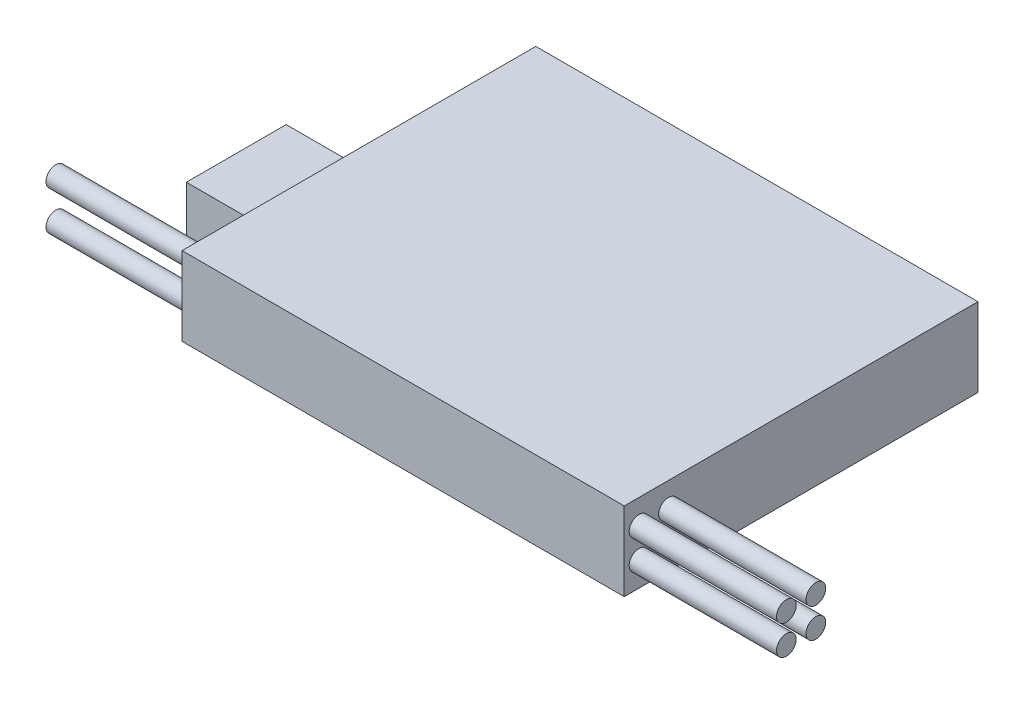
SolidWorks part; units mm, degrees
ref_plane "Plan de face" through (0, 0, 0) normal (0, 0, 1) x (1, 0, 0)
ref_plane "Plan de dessus" through (0, 0, 0) normal (0, 1, 0) x (1, 0, 0)
ref_plane "Plan de droite" through (0, 0, 0) normal (1, 0, 0) x (0, 0, -1)
sketch "Esquisse1" plane through (0, 0, 0) normal (0, 1, 0) x (1, 0, 0)
  line L1 (-22.5, 18) -> (22.5, 18)
  line L2 (-22.5, 18) -> (-22.5, -18)
  line L3 (-22.5, -18) -> (22.5, -18)
  line L4 (22.5, 18) -> (22.5, -18)
  point P4 (0, 18)
  point P6 (-22.5, 0)
  dimension "D1" = 36
  dimension "D2" = 45
extrude "Boss.-Extru.1" add sketch "Esquisse1" along normal blind 8
sketch "Esquisse2" plane through (-22.5, 0, 0) normal (-1, 0, 0) x (0, 0, 1)
  line L0 (18, 8) -> (18, 0) construction
  line L1 (1.4022, 7.81) -> (11.5622, 7.81)
  line L2 (1.4022, 7.81) -> (1.4022, 0.19)
  line L3 (1.4022, 0.19) -> (11.5622, 0.19)
  line L4 (11.5622, 7.81) -> (11.5622, 0.19)
  point P6 (18, 4)
  point P7 (11.5622, 4)
  dimension "D1" = 7.62
  dimension "D2" = 10.16
extrude "Boss.-Extru.2" add sketch "Esquisse2" along normal blind 6
sketch "Esquisse3" plane through (-22.5, 0, 0) normal (-1, 0, 0) x (0, 0, 1)
  line L0 (18, 4) -> (14.1664, 4) construction
  line L1 (18, 8) -> (18, 0) construction
  circle A0 centre (15.846, 6) radius 1
  circle A2 centre (15.846, 2) radius 1
  dimension "D1" = 2
  dimension "D2" = 4
extrude "Boss.-Extru.3" add sketch "Esquisse3" along normal blind 15
sketch "Esquisse4" plane through (22.5, 0, 0) normal (1, 0, 0) x (0, 0, -1)
  line L0 (-18, 4) -> (-15, 4) construction
  line L1 (-18, 8) -> (-18, 0) construction
  line L2 (-15, 8) -> (-15, 0) construction
  line L3 (-18, 8) -> (18, 8) construction
  line L4 (-18, 0) -> (18, 0) construction
  circle A0 centre (-16.5, 5.5) radius 1
  circle A2 centre (-16.5, 2.5) radius 1
  circle A3 centre (-13.5, 2.5) radius 1
  circle A4 centre (-13.5, 5.5) radius 1
  point P3 (-16.5, 4)
  dimension "D2" = 2
  dimension "D1" = 3
  dimension "D3" = 3
extrude "Boss.-Extru.4" add sketch "Esquisse4" along normal blind 15
equation "\"D1@Esquisse2\"=2.54*3"
equation "\"D2@Esquisse2\"=4*2.54"
equation "\"D3@Esquisse4\"=\"D1@Esquisse4\""
